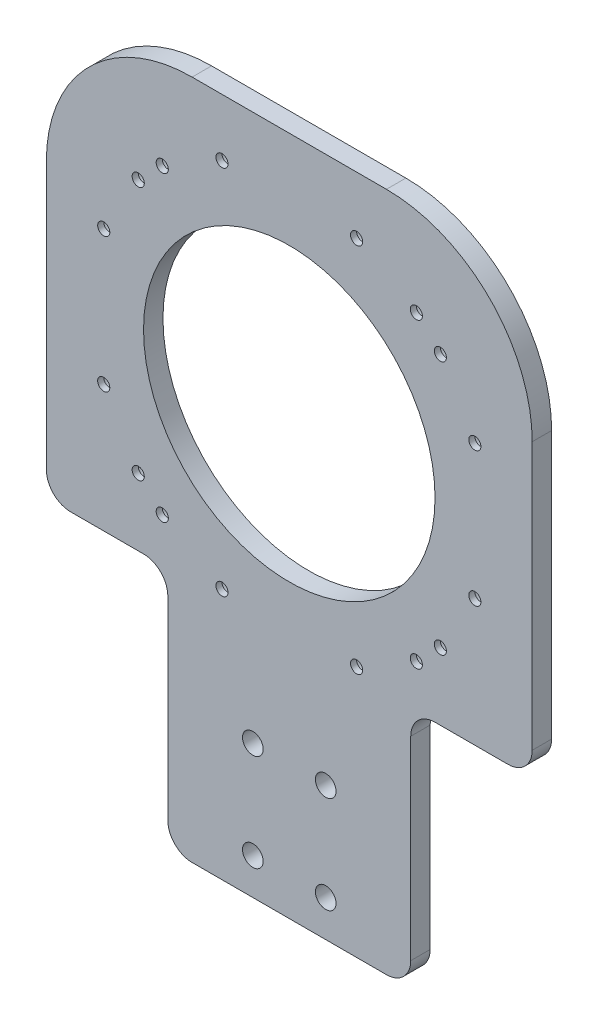
SolidWorks part; units mm, degrees
ref_plane "前视基准面" through (0, 0, 0) normal (0, 0, 1) x (1, 0, 0)
ref_plane "上视基准面" through (0, 0, 0) normal (0, 1, 0) x (1, 0, 0)
ref_plane "右视基准面" through (0, 0, 0) normal (1, 0, 0) x (0, 0, -1)
other "Configuration Table"
sketch "草图1" plane through (0, 0, 0) normal (0, 0, 1) x (1, 0, 0)
  line L0 (0, 0) -> (0, 498.031) construction
  line L1 (100, 0) -> (-100, 0)
  line L2 (-100, 0) -> (-100, 400)
  line L3 (-100, 400) -> (100, 400)
  line L4 (100, 0) -> (100, 400)
  point P7 (0, 400)
  dimension "D1" = 400
  dimension "D2" = 100
extrude "凸台-拉伸1" add sketch "草图1" along normal blind 8
sketch "草图2" plane through (0, 0, 0) normal (0, 0, -1) x (-1, 0, 0)
  line L0 (100, 0) -> (-100, 0) construction
  circle A0 centre (0, 300) radius 60
  circle A1 centre (0, 300) radius 81.25 construction
  dimension "D1" = 120
  dimension "D3" = 162.5
  dimension "D2" = 300
extrude "切除-拉伸1" cut sketch "草图2" against normal blind 10
fillet "圆角1" radius 60 2 edges at (-100, 400, 4) (100, 400, 4)
sketch "草图5" plane through (0, 0, 0) normal (0, 0, -1) x (-1, 0, 0)
  line L0 (0, 0) -> (0, 253.7158) construction
  line L2 (100, 0) -> (-100, 0) construction
  circle A0 centre (-15, 25) radius 4.25
  circle A1 centre (15, 25) radius 4.25
  circle A2 centre (-15, 65) radius 4.25
  circle A3 centre (15, 65) radius 4.25
  circle A4 centre (-15, 175) radius 4.25
  circle A5 centre (15, 135) radius 4.25
  circle A6 centre (-15, 135) radius 4.25
  circle A7 centre (15, 175) radius 4.25
  dimension "D1" = 8.5
  dimension "D2" = 25
  dimension "D3" = 40
  dimension "D4" = 30
  dimension "D5" = 70
  dimension "D8" = 2
extrude "切除-拉伸4" cut sketch "草图5" against normal blind 10
sketch "草图6" plane through (0, 0, 0) normal (0, 0, -1) x (-1, 0, 0)
  line L0 (0, 0) -> (0, 341.2938) construction
  line L1 (100, 0) -> (-100, 0) construction
  line L3 (100, 0) -> (50, 0)
  line L4 (100, 0) -> (100, 220)
  line L5 (100, 220) -> (50, 220)
  line L6 (50, 0) -> (50, 220)
  line L7 (-100, 0) -> (-50, 0)
  line L8 (-100, 0) -> (-100, 220)
  line L9 (-100, 220) -> (-50, 220)
  line L10 (-50, 0) -> (-50, 220)
  dimension "D1" = 50
  dimension "D2" = 50
  dimension "D3" = 220
  dimension "D4" = 220
extrude "切除-拉伸5" cut sketch "草图6" against normal blind 10
fillet "圆角2" radius 10 4 edges at (-50, 220, 4) (-100, 220, 4) (50, 220, 4) (100, 220, 4)
sketch "草图7" plane through (0, 0, 0) normal (0, 0, -1) x (-1, 0, 0)
  arc A0 (64.6844, 352.2941) -> (59.6844, 352.2941) centre (62.1844, 352.2941) ccw construction
  arc A1 (54.7941, 362.1844) -> (49.7941, 362.1844) centre (52.2941, 362.1844) ccw construction
  arc A2 (30.2062, 376.3802) -> (25.2062, 376.3802) centre (27.7062, 376.3802) ccw construction
  arc A3 (-25.2062, 376.3802) -> (-30.2062, 376.3802) centre (-27.7062, 376.3802) ccw construction
  arc A4 (-49.7941, 362.1844) -> (-54.7941, 362.1844) centre (-52.2941, 362.1844) ccw construction
  arc A5 (-64.6844, 352.2941) -> (-59.6844, 352.2941) centre (-62.1844, 352.2941) ccw construction
  arc A6 (-78.8802, 272.2938) -> (-73.8802, 272.2938) centre (-76.3802, 272.2938) ccw construction
  arc A7 (-64.6844, 247.7059) -> (-59.6844, 247.7059) centre (-62.1844, 247.7059) ccw construction
  arc A8 (-54.7941, 237.8156) -> (-49.7941, 237.8156) centre (-52.2941, 237.8156) ccw construction
  arc A9 (-30.2062, 223.6198) -> (-25.2062, 223.6198) centre (-27.7062, 223.6198) ccw construction
  arc A10 (25.2062, 223.6198) -> (30.2062, 223.6198) centre (27.7062, 223.6198) ccw construction
  arc A11 (49.7941, 237.8156) -> (54.7941, 237.8156) centre (52.2941, 237.8156) ccw construction
  arc A12 (64.6844, 247.7059) -> (59.6844, 247.7059) centre (62.1844, 247.7059) ccw construction
  arc A13 (78.8802, 272.2938) -> (73.8802, 272.2938) centre (76.3802, 272.2938) ccw construction
  arc A14 (78.8802, 327.7062) -> (73.8802, 327.7062) centre (76.3802, 327.7062) ccw construction
  arc A15 (64.6844, 352.2941) -> (59.6844, 352.2941) centre (62.1844, 352.2941) ccw construction
  arc A16 (54.7941, 362.1844) -> (49.7941, 362.1844) centre (52.2941, 362.1844) ccw construction
  arc A17 (30.2062, 376.3802) -> (25.2062, 376.3802) centre (27.7062, 376.3802) ccw construction
  arc A18 (-25.2062, 376.3802) -> (-30.2062, 376.3802) centre (-27.7062, 376.3802) ccw construction
  arc A19 (-49.7941, 362.1844) -> (-54.7941, 362.1844) centre (-52.2941, 362.1844) ccw construction
  arc A20 (-64.6844, 352.2941) -> (-59.6844, 352.2941) centre (-62.1844, 352.2941) ccw construction
  arc A21 (-78.8802, 272.2938) -> (-73.8802, 272.2938) centre (-76.3802, 272.2938) ccw construction
  arc A22 (-64.6844, 247.7059) -> (-59.6844, 247.7059) centre (-62.1844, 247.7059) ccw construction
  arc A23 (-54.7941, 237.8156) -> (-49.7941, 237.8156) centre (-52.2941, 237.8156) ccw construction
  arc A24 (-30.2062, 223.6198) -> (-25.2062, 223.6198) centre (-27.7062, 223.6198) ccw construction
  arc A25 (25.2062, 223.6198) -> (30.2062, 223.6198) centre (27.7062, 223.6198) ccw construction
  arc A26 (49.7941, 237.8156) -> (54.7941, 237.8156) centre (52.2941, 237.8156) ccw construction
  arc A27 (64.6844, 247.7059) -> (59.6844, 247.7059) centre (62.1844, 247.7059) ccw construction
  arc A28 (78.8802, 272.2938) -> (73.8802, 272.2938) centre (76.3802, 272.2938) ccw construction
  arc A29 (78.8802, 327.7062) -> (73.8802, 327.7062) centre (76.3802, 327.7062) ccw construction
  arc A30 (-73.8802, 327.7062) -> (-78.8802, 327.7062) centre (-76.3802, 327.7062) ccw construction
  arc A31 (-73.8802, 327.7062) -> (-78.8802, 327.7062) centre (-76.3802, 327.7062) ccw construction
  circle A32 centre (27.7062, 376.3802) radius 2.5
  circle A33 centre (52.2941, 362.1844) radius 2.5
  circle A34 centre (62.1844, 352.2941) radius 2.5
  circle A35 centre (76.3802, 327.7062) radius 2.5
  circle A36 centre (76.3802, 272.2938) radius 2.5
  circle A37 centre (62.1844, 247.7059) radius 2.5
  circle A38 centre (52.2941, 237.8156) radius 2.5
  circle A39 centre (27.7062, 223.6198) radius 2.5
  circle A40 centre (-27.7062, 223.6198) radius 2.5
  circle A41 centre (-52.2941, 237.8156) radius 2.5
  circle A42 centre (-62.1844, 247.7059) radius 2.5
  circle A43 centre (-76.3802, 272.2938) radius 2.5
  circle A44 centre (-76.3802, 327.7062) radius 2.5
  circle A45 centre (-62.1844, 352.2941) radius 2.5
  circle A46 centre (-52.2941, 362.1844) radius 2.5
  circle A47 centre (-27.7062, 376.3802) radius 2.5
extrude "切除-拉伸6" cut sketch "草图7" against normal blind 69
sketch "草图8" plane through (0, 0, 0) normal (0, 0, -1) x (-1, 0, 0)
  circle A0 centre (27.7062, 376.3802) radius 6
  circle A1 centre (52.2941, 362.1844) radius 6
  circle A2 centre (62.1844, 352.2941) radius 6
  circle A3 centre (76.3802, 327.7062) radius 6
  circle A4 centre (76.3802, 272.2938) radius 6
  circle A5 centre (62.1844, 247.7059) radius 6
  circle A6 centre (52.2941, 237.8156) radius 6
  circle A7 centre (27.7062, 223.6198) radius 6
  circle A8 centre (-27.7062, 223.6198) radius 6
  circle A9 centre (-52.2941, 237.8156) radius 6
  circle A10 centre (-62.1844, 247.7059) radius 6
  circle A11 centre (-76.3802, 272.2938) radius 6
  circle A12 centre (-76.3802, 327.7062) radius 6
  circle A13 centre (-62.1844, 352.2941) radius 6
  circle A14 centre (-52.2941, 362.1844) radius 6
  circle A15 centre (-27.7062, 376.3802) radius 6
  dimension "D1" = 12
extrude "切除-拉伸7" cut sketch "草图8" against normal blind 5.5
sketch "草图9" plane through (0, 0, 0) normal (0, 0, -1) x (-1, 0, 0)
  line L0 (-50, 0) -> (-50, 210) construction
  line L1 (50, 0) -> (-50, 0)
  line L2 (50, 0) -> (50, 120)
  line L3 (50, 120) -> (-50, 120)
  line L4 (-50, 0) -> (-50, 120)
  dimension "D1" = 120
extrude "切除-拉伸8" cut sketch "草图9" against normal blind 10
fillet "圆角3" radius 10 2 edges at (50, 120, 4) (-50, 120, 4)
